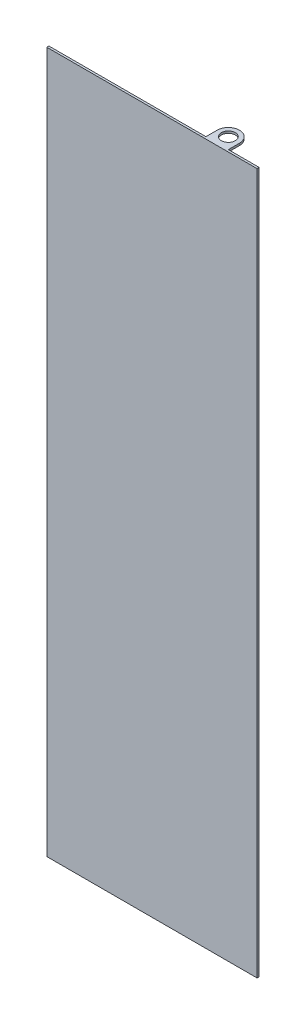
SolidWorks part; units mm, degrees
ref_plane "Front Plane" through (0, 0, 0) normal (0, 0, 1) x (1, 0, 0)
ref_plane "Top Plane" through (0, 0, 0) normal (0, 1, 0) x (1, 0, 0)
ref_plane "Right Plane" through (0, 0, 0) normal (1, 0, 0) x (0, 0, -1)
sketch "Sketch2" plane through (0, 0, 0) normal (0, 0, 1) x (1, 0, 0)
  line L1 (-75, 250) -> (75, 250)
  line L2 (-75, 250) -> (-75, -250)
  line L3 (-75, -250) -> (75, -250)
  line L4 (75, 250) -> (75, -250)
  line L5 (-75, 250) -> (75, -250) construction
  line L6 (-75, -250) -> (75, 250) construction
  point P0 (0, 0)
  dimension "D1" = 150
  dimension "D2" = 500
extrude "Boss-Extrude1" add sketch "Sketch2" along normal blind 1.5
sketch "Sketch3" plane through (0, 250, 0) normal (0, 1, 0) x (1, 0, 0)
  line L0 (45, -0.7236) -> (45, 8) construction
  line L1 (37, 0) -> (37, 8)
  line L2 (53, 0) -> (53, 8)
  line L3 (75, 0) -> (-75, 0) construction
  line L4 (53, 0) -> (37, 0)
  arc A1 (53, 8) -> (37, 8) centre (45, 8) ccw
  circle A2 centre (45, 8) radius 5
  point P2 (-45, 2.6318)
  dimension "D2" = 16
  dimension "D3" = 8
  dimension "D1" = 45
  dimension "D4" = 8
  dimension "D5" = 8
extrude "Boss-Extrude2" add sketch "Sketch3" against normal blind 1.5
